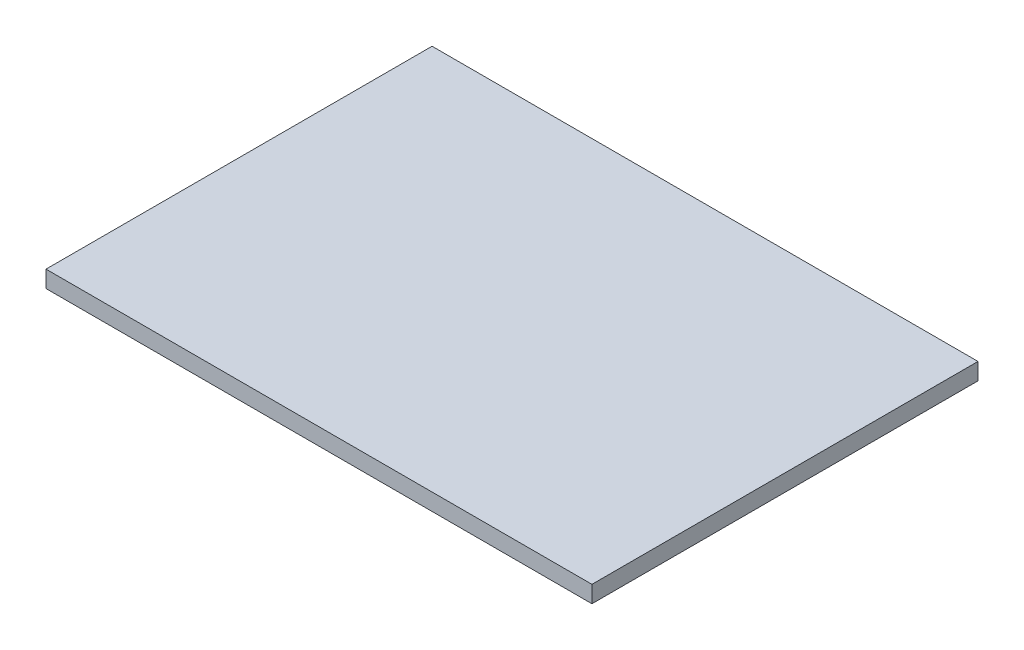
SolidWorks part; units mm, degrees
ref_plane "Front Plane" through (0, 0, 0) normal (0, 0, 1) x (1, 0, 0)
ref_plane "Top Plane" through (0, 0, 0) normal (0, 1, 0) x (1, 0, 0)
ref_plane "Right Plane" through (0, 0, 0) normal (1, 0, 0) x (0, 0, -1)
sketch "Sketch1" plane through (0, 0, 0) normal (0, 1, 0) x (1, 0, 0)
  line L1 (-105, -74.25) -> (105, -74.25)
  line L2 (-105, -74.25) -> (-105, 74.25)
  line L3 (-105, 74.25) -> (105, 74.25)
  line L4 (105, -74.25) -> (105, 74.25)
  line L5 (-105, -74.25) -> (105, 74.25) construction
  line L6 (-105, 74.25) -> (105, -74.25) construction
  point P0 (0, 0)
  dimension "D1" = 210
  dimension "D2" = 148.5
extrude "Boss-Extrude1" add sketch "Sketch1" along normal blind 10
sketch "Sketch2" plane through (0, 0, 74.25) normal (0, 0, 1) x (1, 0, 0)
  line L0 (105, 10) -> (105, 0) construction
  line L1 (-105, 10) -> (105, 10)
  line L2 (-105, 10) -> (-105, 6.478)
  line L3 (-105, 6.478) -> (105, 6.478)
  line L4 (105, 10) -> (105, 6.478)
extrude "Cut-Extrude1" cut sketch "Sketch2" against normal through all both and the other way through all
